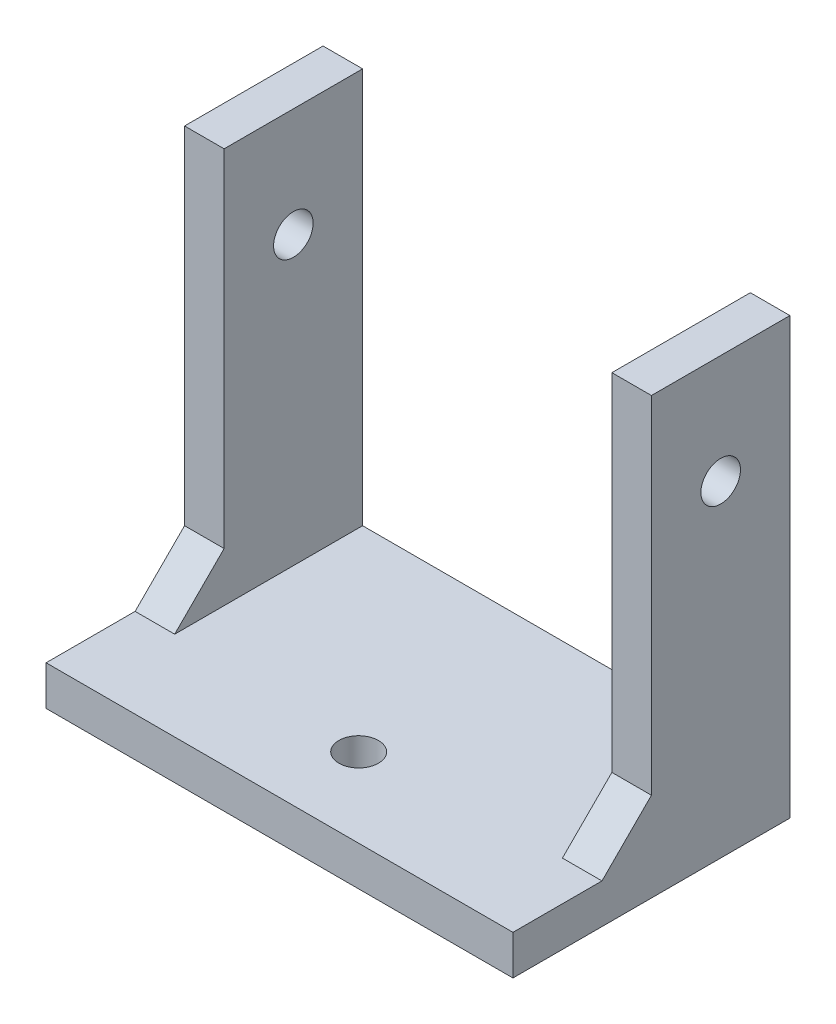
SolidWorks part; units mm, degrees
ref_plane "Front Plane" through (0, 0, 0) normal (0, 0, 1) x (1, 0, 0)
ref_plane "Top Plane" through (0, 0, 0) normal (0, 1, 0) x (1, 0, 0)
ref_plane "Right Plane" through (0, 0, 0) normal (1, 0, 0) x (0, 0, -1)
sketch "Sketch1" plane through (0, 0, 0) normal (0, 1, 0) x (1, 0, 0)
  line L1 (11.8, -7) -> (-11.8, -7)
  line L2 (11.8, -7) -> (11.8, 7)
  line L3 (11.8, 7) -> (-11.8, 7)
  line L4 (-11.8, -7) -> (-11.8, 7)
  line L5 (11.8, -7) -> (-11.8, 7) construction
  line L6 (11.8, 7) -> (-11.8, -7) construction
  point P0 (0, 0)
  dimension "D1" = 23.6
  dimension "D2" = 14
extrude "Boss-Extrude1" add sketch "Sketch1" along normal blind 2
sketch "Sketch2" plane through (11.8, 0, 0) normal (1, 0, 0) x (0, 0, -1)
  line L0 (-7, 0) -> (7, 0) construction
  line L1 (7, 2) -> (0, 2)
  line L2 (7, 2) -> (7, 22)
  line L3 (7, 22) -> (0, 22)
  line L4 (0, 4.5) -> (0, 22)
  line L5 (0, 4.5) -> (-2.5, 2)
  line L6 (-7, 2) -> (7, 2) construction
  line L7 (0, 2) -> (-2.5, 2)
  dimension "D1" = 7
  dimension "D2" = 22
  dimension "D3" = 2.5
  dimension "D4" = 2.5
extrude "Boss-Extrude2" add sketch "Sketch2" against normal blind 2
sketch "Sketch3" plane through (-11.8, 0, 0) normal (-1, 0, 0) x (0, 0, 1)
  line L5 (-7, 22) -> (-7, 2)
  line L6 (-7, 2) -> (2.5, 2)
  line L7 (2.5, 2) -> (0, 4.5)
  line L8 (0, 4.5) -> (0, 22)
  line L9 (0, 22) -> (-7, 22)
  line L10 (-7, 22) -> (-7, 2)
  line L11 (-7, 2) -> (2.5, 2)
  line L12 (2.5, 2) -> (0, 4.5)
  line L13 (0, 4.5) -> (0, 22)
  line L14 (0, 22) -> (-7, 22)
  dimension "D1" = 0
extrude "Boss-Extrude3" add sketch "Sketch3" against normal blind 2
sketch "Sketch4" plane through (0, 0, 0) normal (0, -1, 0) x (1, 0, 0)
  line L0 (-11.8, 7) -> (11.8, 7) construction
  circle A0 centre (0, 3) radius 1
  dimension "D2" = 2
  dimension "D1" = 4
extrude "Cut-Extrude1" cut sketch "Sketch4" against normal blind 2
sketch "Sketch5" plane through (11.8, 0, 0) normal (1, 0, 0) x (0, 0, -1)
  line L0 (7, 22) -> (0, 22) construction
  circle A0 centre (3.5, 16.5) radius 1
  dimension "D2" = 2
  dimension "D1" = 5.5
extrude "Cut-Extrude2" cut sketch "Sketch5" against normal through all
